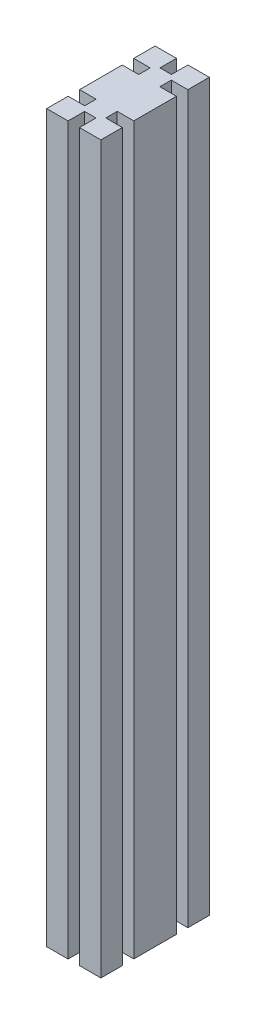
SolidWorks part; units mm, degrees
ref_plane "Front Plane" through (0, 0, 0) normal (0, 0, 1) x (1, 0, 0)
ref_plane "Top Plane" through (0, 0, 0) normal (0, 1, 0) x (1, 0, 0)
ref_plane "Right Plane" through (0, 0, 0) normal (1, 0, 0) x (0, 0, -1)
sketch "Sketch1" plane through (0, 0, 0) normal (0, 1, 0) x (1, 0, 0)
  line L0 (0, 0) -> (-18.9548, 0) construction
  line L1 (-18.9548, -37.9412) -> (18.9548, -37.9412)
  line L2 (-18.9548, -37.9412) -> (-18.9548, 37.9412)
  line L3 (-18.9548, 37.9412) -> (18.9548, 37.9412)
  line L4 (18.9548, -37.9412) -> (18.9548, 37.9412)
  line L5 (-18.9548, -37.9412) -> (18.9548, 37.9412) construction
  line L6 (-18.9548, 37.9412) -> (18.9548, -37.9412) construction
  line L7 (0, 0) -> (0, -37.9412) construction
  line L8 (-7.3977, 22.9362) -> (-7.3977, 14.9225)
  line L9 (-18.9548, -22.9362) -> (-7.3977, -22.9362)
  line L10 (-18.9548, -22.9362) -> (-18.9548, -14.9225)
  line L11 (-18.9548, -14.9225) -> (-7.3977, -14.9225)
  line L12 (-7.3977, -22.9362) -> (-7.3977, -14.9225)
  line L13 (4.0068, -26.3842) -> (-4.0069, -26.3842)
  line L14 (4.0068, -26.3842) -> (4.0069, -37.9412)
  line L15 (4.0069, -37.9412) -> (-4.0069, -37.9412)
  line L16 (-4.0069, -26.3842) -> (-4.0069, -37.9412)
  line L17 (4.0068, -26.3842) -> (-4.0069, -37.9412) construction
  line L18 (4.0069, -37.9412) -> (-4.0069, -26.3842) construction
  line L19 (-18.9548, 14.9225) -> (-7.3977, 14.9225)
  line L20 (-18.9547, 22.9362) -> (-18.9548, 14.9225)
  line L21 (-18.9547, 22.9362) -> (-7.3977, 22.9362)
  line L22 (4.0069, 37.9412) -> (-4.0068, 26.3842) construction
  line L23 (4.0069, 26.3842) -> (-4.0068, 37.9412) construction
  line L24 (-4.0068, 26.3842) -> (-4.0068, 37.9412)
  line L25 (4.0069, 37.9412) -> (-4.0068, 37.9412)
  line L26 (4.0069, 26.3842) -> (4.0069, 37.9412)
  line L27 (4.0069, 26.3842) -> (-4.0068, 26.3842)
  line L28 (18.9548, 22.9362) -> (7.3978, 22.9362)
  line L29 (18.9548, 22.9362) -> (18.9548, 14.9225)
  line L30 (18.9548, 14.9225) -> (7.3978, 14.9225)
  line L31 (7.3978, 22.9362) -> (7.3978, 14.9225)
  line L32 (7.3978, -22.9362) -> (7.3978, -14.9225)
  line L33 (18.9548, -14.9225) -> (7.3978, -14.9225)
  line L34 (18.9548, -22.9362) -> (18.9548, -14.9225)
  line L35 (18.9548, -22.9362) -> (7.3978, -22.9362)
  point P0 (0, 0)
  point P13 (0, -32.1627)
  point P26 (0, 32.1627)
  dimension "D1" = 37.9095
  dimension "D2" = 75.8825
  dimension "D3" = 29.845
  dimension "D4" = 8.0137
  dimension "D5" = 11.557
extrude "Boss-Extrude1" add sketch "Sketch1" along normal blind 508 contours L4 L35 L32 L33 L30 L31 L28 L3 L26 L27 L24 L2 L21 L8 L19 L11 L12 L9 L1 L16 L13 L14
